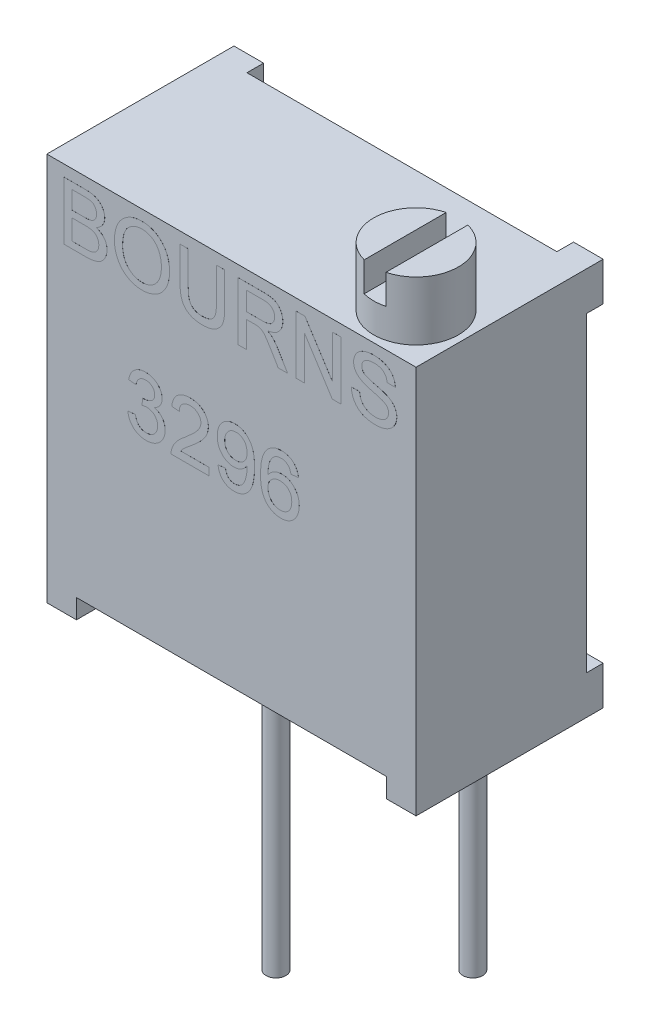
SolidWorks part; units mm, degrees
ref_plane "Plane1" through (0, 0, 0) normal (0, 0, 1) x (1, 0, 0)
ref_plane "Plane2" through (0, 0, 0) normal (0, 1, 0) x (1, 0, 0)
ref_plane "Plane3" through (0, 0, 0) normal (1, 0, 0) x (0, 0, -1)
sketch "Sketch1" plane through (0, 0, 0) normal (0, 0, 1) x (1, 0, 0)
  line L1 (-4.765, 0) -> (4.765, 0)
  line L2 (-4.765, 0) -> (-4.765, 10.03)
  line L3 (-4.765, 10.03) -> (4.765, 10.03)
  line L4 (4.765, 0) -> (4.765, 10.03)
  dimension "D1" = 9.53
  dimension "D2" = 10.03
extrude "Extrude1" add sketch "Sketch1" along normal blind 4.4
sketch "Sketch2" plane through (0, 0, 4.4) normal (0, 0, 1) x (1, 0, 0)
  line L0 (-4.765, 0) -> (4.765, 0) construction
  line L1 (-4, 0) -> (4, 0)
  line L2 (-4, 0) -> (-4, 0.5)
  line L3 (-4, 0.5) -> (4, 0.5)
  line L4 (4, 0) -> (4, 0.5)
  dimension "D1" = 8
  dimension "D2" = 0.5
extrude "Cut-Extrude1" cut sketch "Sketch2" against normal through all
sketch "Sketch3" plane through (0, 0, 0) normal (0, 0, -1) x (-1, 0, 0)
  line L1 (-4.765, 0) -> (-4, 0)
  line L2 (-4.765, 0) -> (-4.765, 1)
  line L3 (-4.765, 1) -> (-4, 1)
  line L4 (-4, 0) -> (-4, 1)
  line L5 (4.765, 0) -> (4, 0)
  line L6 (4.765, 0) -> (4.765, 1)
  line L7 (4.765, 1) -> (4, 1)
  line L8 (4, 0) -> (4, 1)
  line L9 (4.765, 10.03) -> (4, 10.03)
  line L10 (4.765, 10.03) -> (4.765, 9.03)
  line L11 (4.765, 9.03) -> (4, 9.03)
  line L12 (4, 10.03) -> (4, 9.03)
  line L13 (-4.765, 10.03) -> (-4, 10.03)
  line L14 (-4.765, 10.03) -> (-4.765, 9.03)
  line L15 (-4.765, 9.03) -> (-4, 9.03)
  line L16 (-4, 10.03) -> (-4, 9.03)
  dimension "D1" = 1
  dimension "D2" = 1
extrude "Extrude2" add sketch "Sketch3" along normal blind 0.43
sketch "Sketch4" plane through (0, 0.5, 0) normal (0, -1, 0) x (1, 0, 0)
  line L0 (0, 0) -> (0, 1.98) construction
  line L1 (-2.54, 1.98) -> (2.54, 1.98) construction
  line L2 (4.765, -0.43) -> (4, -0.43) construction
  circle A0 centre (2.54, 1.98) radius 0.255
  circle A1 centre (0, 1.98) radius 0.255
  circle A2 centre (-2.54, 1.98) radius 0.255
  dimension "D4" = 0.51
  dimension "D1" = 2.41
  dimension "D2" = 2.54
  dimension "D3" = 2.54
sketch "Sketch5" plane through (0, 10.03, 0) normal (0, 1, 0) x (-1, 0, 0)
  line L0 (-4.765, 4.4) -> (4.765, 4.4) construction
  line L1 (-4.765, 4.4) -> (-4.765, -0.43) construction
  circle A0 centre (-3.495, 3.13) radius 1.095
  dimension "D3" = 2.19
  dimension "D1" = 1.27
  dimension "D2" = 1.27
extrude "Extrude4" add sketch "Sketch5" along normal blind 1.52
sketch "Sketch6" plane through (0, 11.55, 0) normal (0, 1, 0) x (-1, 0, 0)
  line L0 (-3.495, 3.13) -> (-3.495, 1.593) construction
  line L1 (-3.215, 1.593) -> (-3.775, 1.593)
  line L2 (-3.215, 1.593) -> (-3.215, 4.7702)
  line L3 (-3.215, 4.7702) -> (-3.775, 4.7702)
  line L4 (-3.775, 1.593) -> (-3.775, 4.7702)
  dimension "D1" = 0.56
extrude "Cut-Extrude2" cut sketch "Sketch6" against normal blind 0.76
sketch "Sketch7" plane through (0, 0, 4.4) normal (0, 0, 1) x (1, 0, 0)
  text T0 "BOURNS\r\n   3296" font "Arial" height 1.5
extrude "Extrude5" add sketch "Sketch7" along normal blind 0.001
sketch "Sketch9" plane through (0, 0.5, 0) normal (0, -1, 0) x (1, 0, 0)
  line L0 (-2.54, 0.71) -> (2.54, 0.71) construction
  line L1 (0, 0) -> (0, 3.25) construction
  line L2 (-4, -0.43) -> (-4.765, -0.43) construction
  circle A0 centre (-2.54, 0.71) radius 0.255
  circle A1 centre (0, 3.25) radius 0.255
  circle A2 centre (2.54, 0.71) radius 0.255
  dimension "D5" = 0.51
  dimension "D1" = 1.14
  dimension "D2" = 2.54
  dimension "D3" = 2.54
  dimension "D4" = 2.54
extrude "Extrude7" add sketch "Sketch9" along normal blind 6.9
